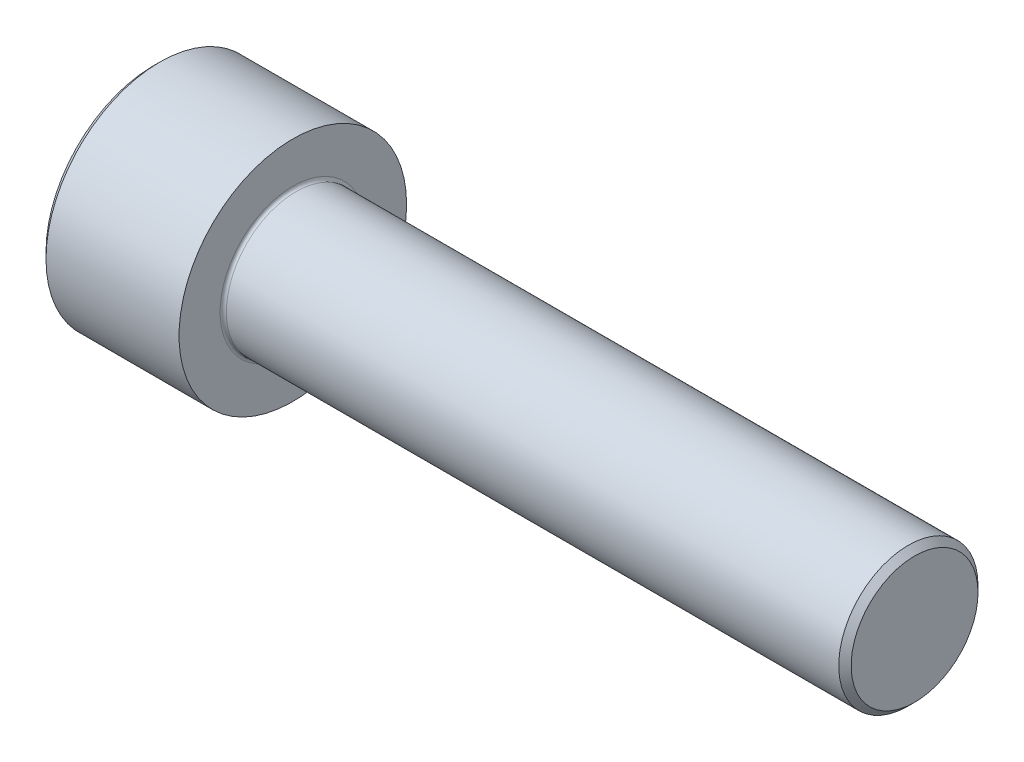
SolidWorks part; units mm, degrees
material "Alloy Steel"
ref_plane "Z Plane" through (0, 0, 0) normal (0, 0, 1) x (1, 0, 0)
ref_plane "Y Plane" through (0, 0, 0) normal (0, 1, 0) x (1, 0, 0)
ref_plane "X Plane" through (0, 0, 0) normal (1, 0, 0) x (0, 0, -1)
sketch "Sketch1" plane through (0, 0, 0) normal (0, 1, 0) x (1, 0, 0)
  line L0 (0, 2.3241) -> (0, -2.3241) construction
  line L1 (0, 0) -> (0, 2.3241)
  line L2 (0, 2.3241) -> (2.8448, 2.3241)
  line L3 (2.8448, 2.3241) -> (2.8448, 1.4224)
  line L4 (2.8448, 1.4224) -> (15.5448, 1.4224)
  line L5 (15.5448, 1.4224) -> (15.5448, -1.4224) construction
  line L6 (15.5448, 1.4224) -> (15.5448, 0)
  line L7 (15.5448, 0) -> (0, 0)
  line L8 (0, -2.3241) -> (0.9483, -2.3241) construction
  line L9 (0.9483, -2.3241) -> (1.8965, -2.3241) construction
  line L10 (1.8965, -2.3241) -> (2.8448, -2.3241) construction
  point P2 (0, 0)
  point P5 (15.5448, 0)
  dimension "Head Diameter" = 4.6482
  dimension "Thread Diameter" = 2.8448
  dimension "Thread Length" = 12.7
revolve "Body" add sketch "Sketch1" angle 360 about L7
cosmetic thread "Cosmetic Thread1" parameters "D1"=12.7, "D2"=2.065
ref_plane "Plane1" through (1.8965, 0, 0) normal (1, 0, 0) x (0, 0, -1)
sketch "Sketch2" plane through (0, 0, 0) normal (-1, 0, 0) x (0, 0, 1)
  line L1 (-1.3748, 0) -> (-0.6874, -1.1906)
  line L2 (-0.6874, -1.1906) -> (0.6874, -1.1906)
  line L3 (0.6874, -1.1906) -> (1.3748, 0)
  line L4 (1.3748, 0) -> (0.6874, 1.1906)
  line L5 (0.6874, 1.1906) -> (-0.6874, 1.1906)
  line L6 (-0.6874, 1.1906) -> (-1.3748, 0)
  circle A0 centre (0, 0) radius 1.1906 construction
  dimension "Hex Head" = 2.3813
extrude "Hex" cut sketch "Sketch2" against normal up to surface (1.8965 mm away)
chamfer "Chamfer1" distance 0.127 angle 45 2 edges at (15.5448, 0, -1.4224) (0, 0, -2.3241)
fillet "Fillet1" radius 0.0635 1 edges at (2.8448, 0, -1.4224)
sketch "Sketch3" plane through (0, 0, 0) normal (1, 0, 0) x (0, 0, -1)
  circle A0 centre (0, 0) radius 1.3748
extrude "Hex Chamfer" cut sketch "Sketch3" along normal blind 2.54 draft 45
